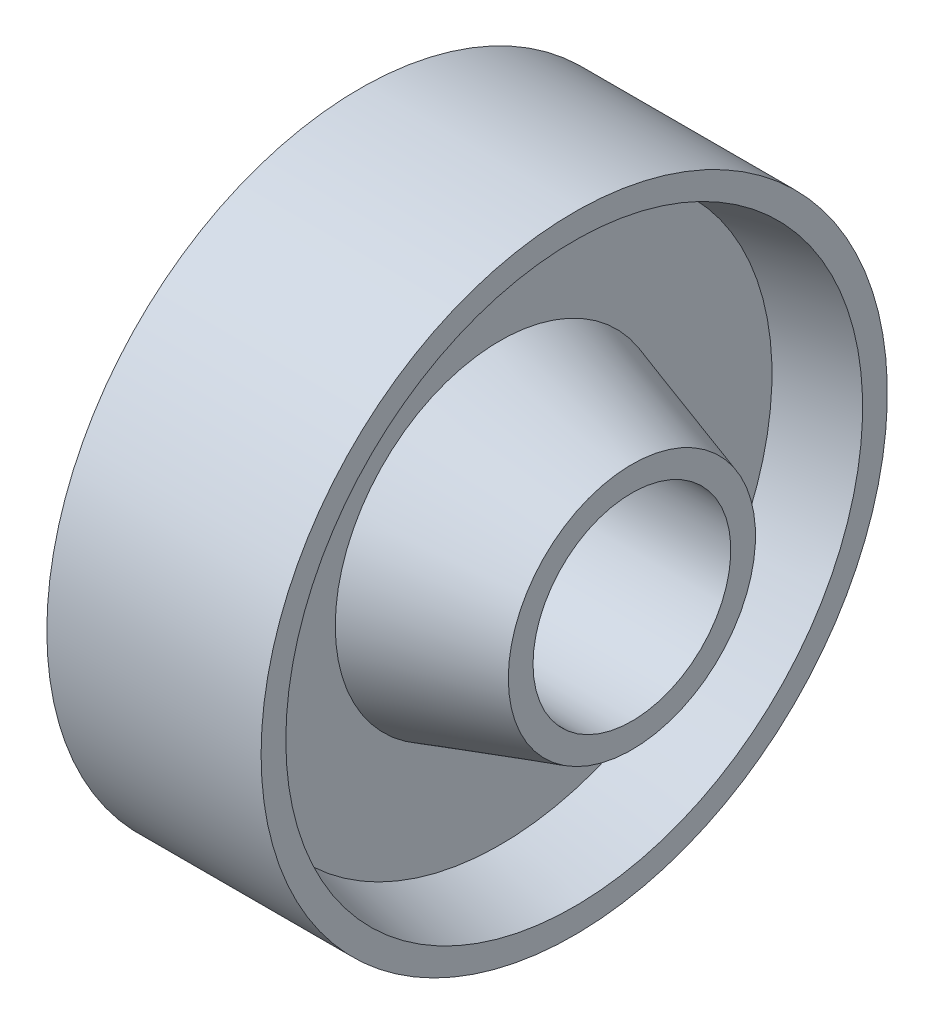
SolidWorks part; units mm, degrees
material "Ductile Iron"
ref_plane "Front Plane" through (0, 0, 0) normal (0, 0, 1) x (1, 0, 0)
ref_plane "Top Plane" through (0, 0, 0) normal (0, 1, 0) x (1, 0, 0)
ref_plane "Right Plane" through (0, 0, 0) normal (1, 0, 0) x (0, 0, -1)
sketch "Sketch1" plane through (0, 0, 0) normal (0, 0, 1) x (1, 0, 0)
  line L0 (0, -44.5786) -> (0, 44.5786) construction
  line L1 (-72.5376, 0) -> (72.5376, 0) construction
  line L2 (13, 38) -> (-13, 38)
  line L3 (-13, 38) -> (-13, 35)
  line L4 (-13, 35) -> (-4, 33)
  line L5 (-4, 33) -> (-4, 20)
  line L6 (-4, 20) -> (-20, 15)
  line L7 (-20, 15) -> (-20, 12)
  line L8 (-20, 12) -> (20, 12)
  line L9 (20, 15) -> (20, 12)
  line L10 (4, 20) -> (20, 15)
  line L11 (4, 33) -> (4, 20)
  line L12 (13, 35) -> (4, 33)
  line L13 (13, 38) -> (13, 35)
  point P4 (0, 0)
  point P8 (0, 0)
  point P10 (-20, 13.5)
  point P17 (-4, 26.5)
  point P18 (-13, 36.5)
  point P20 (0, 12)
  point P25 (0, 38)
  dimension "D1" = 38
  dimension "D2" = 35
  dimension "D3" = 12
  dimension "D4" = 15
  dimension "D5" = 20
  dimension "D6" = 20
  dimension "D7" = 4
  dimension "D8" = 13
  dimension "D9" = 33
revolve "Revolve1" add sketch "Sketch1" angle 360 about L1
